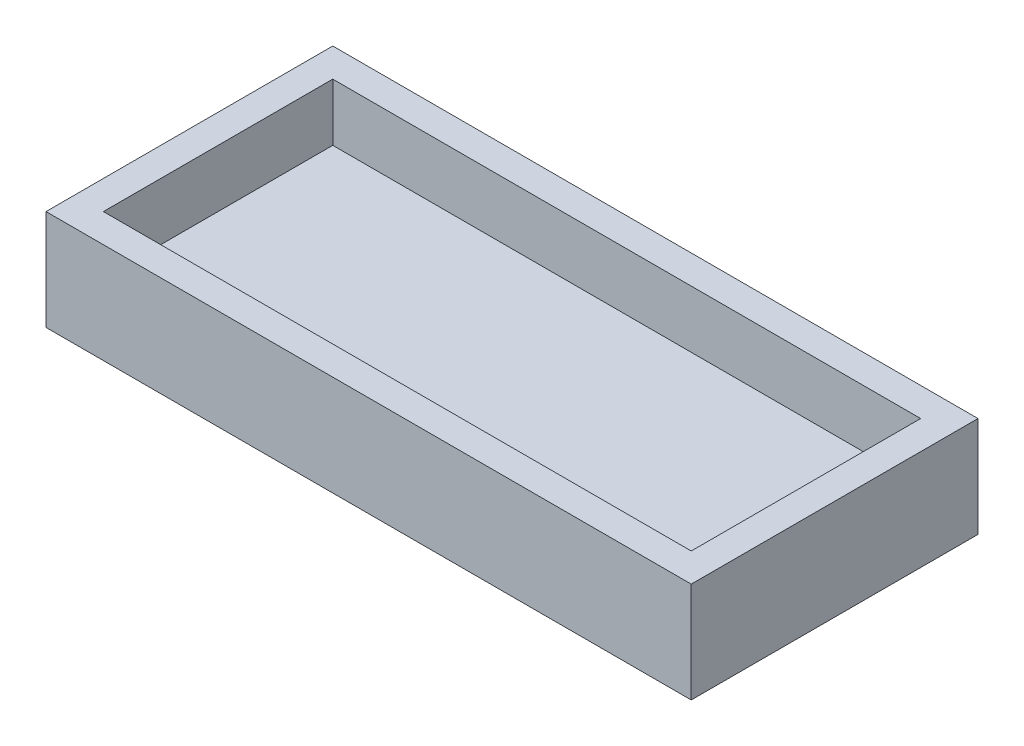
SolidWorks part; units mm, degrees
ref_plane "Front Plane" through (0, 0, 0) normal (0, 0, 1) x (1, 0, 0)
ref_plane "Top Plane" through (0, 0, 0) normal (0, 1, 0) x (1, 0, 0)
ref_plane "Right Plane" through (0, 0, 0) normal (1, 0, 0) x (0, 0, -1)
sketch "Sketch1" plane through (0, 0, 0) normal (0, 1, 0) x (1, 0, 0)
  line L1 (-20.5, 8) -> (20.5, 8)
  line L2 (-20.5, 8) -> (-20.5, -8)
  line L3 (-20.5, -8) -> (20.5, -8)
  line L4 (20.5, 8) -> (20.5, -8)
  line L5 (-20.5, 8) -> (20.5, -8) construction
  line L6 (-20.5, -8) -> (20.5, 8) construction
  point P0 (0, 0)
extrude "Boss-Extrude1" add sketch "Sketch1" along normal blind 3
sketch "Sketch2" plane through (0, 0, 0) normal (0, -1, 0) x (1, 0, 0)
  line L0 (-20.5, -8) -> (-20.5, 8) construction
  line L1 (20.5, -8) -> (-20.5, -8)
  line L2 (20.5, -8) -> (20.5, 8)
  line L3 (20.5, 8) -> (-20.5, 8)
  line L4 (-20.5, -8) -> (-20.5, 8)
  line L9 (22.5, -10) -> (22.5, 10)
  line L14 (22.5, 10) -> (-22.5, 10)
  line L15 (-22.5, -10) -> (-22.5, 10)
  line L16 (22.5, -10) -> (-22.5, -10)
  dimension "D2" = 2
extrude "Boss-Extrude2" add sketch "Sketch2" against normal offset from surface (7 mm away) 4 up to face at (0, 3, 0) offset beyond the face yes
